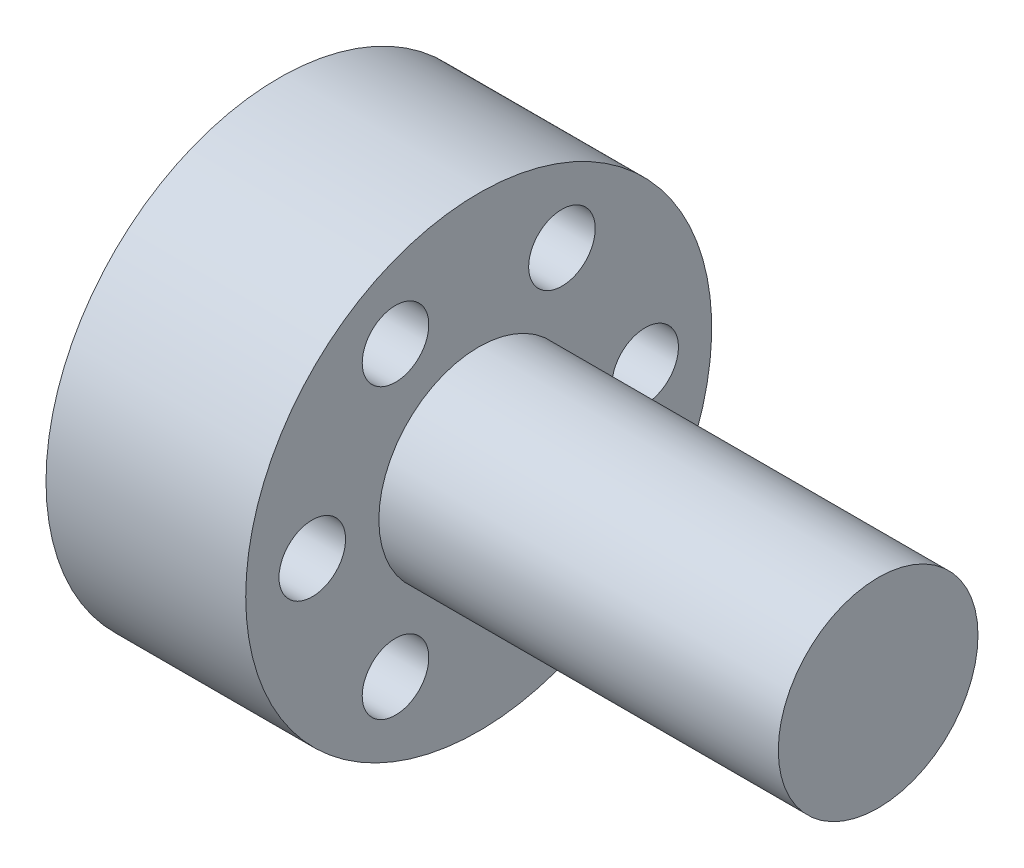
SolidWorks part; units mm, degrees
ref_plane "Спереди" through (0, 0, 0) normal (0, 0, 1) x (1, 0, 0)
ref_plane "Сверху" through (0, 0, 0) normal (0, 1, 0) x (1, 0, 0)
ref_plane "Справа" through (0, 0, 0) normal (1, 0, 0) x (0, 0, -1)
sketch "Эскиз1" plane through (0, 0, 0) normal (0, 0, 1) x (1, 0, 0)
  line L0 (0, 0) -> (100, 0)
  line L1 (0, 0) -> (0, 20)
  line L2 (0, 20) -> (10, 20)
  line L3 (10, 20) -> (10, 35)
  line L4 (10, 35) -> (40, 35)
  line L5 (40, 35) -> (40, 15)
  line L6 (40, 15) -> (100, 15)
  line L7 (100, 0) -> (100, 15)
revolve "Повернуть1" add sketch "Эскиз1" angle 360 about L0
sketch "Эскиз2" plane through (0, 0, 0) normal (1, 0, 0) x (0, 0, -1)
  circle A0 centre (25, 0) radius 5
extrude "Вырез-Вытянуть1" cut sketch "Эскиз2" along normal through all
sketch "Эскиз3" plane through (0, 0, 0) normal (1, 0, 0) x (0, 0, -1)
  circle A0 centre (12.5, 21.6506) radius 5
extrude "Вырез-Вытянуть2" cut sketch "Эскиз3" along normal through all
sketch "Эскиз4" plane through (0, 0, 0) normal (1, 0, 0) x (0, 0, -1)
  circle A0 centre (-12.5, 21.6506) radius 5
extrude "Вырез-Вытянуть3" cut sketch "Эскиз4" along normal through all
sketch "Эскиз5" plane through (0, 0, 0) normal (1, 0, 0) x (0, 0, -1)
  circle A0 centre (-25, 0) radius 5
extrude "Вырез-Вытянуть4" cut sketch "Эскиз5" along normal through all
sketch "Эскиз6" plane through (0, 0, 0) normal (1, 0, 0) x (0, 0, -1)
  circle A0 centre (-12.5, -21.6506) radius 5
extrude "Вырез-Вытянуть5" cut sketch "Эскиз6" along normal through all
sketch "Эскиз7" plane through (0, 0, 0) normal (1, 0, 0) x (0, 0, -1)
  circle A0 centre (12.5, -21.6506) radius 5
extrude "Вырез-Вытянуть6" cut sketch "Эскиз7" along normal through all
